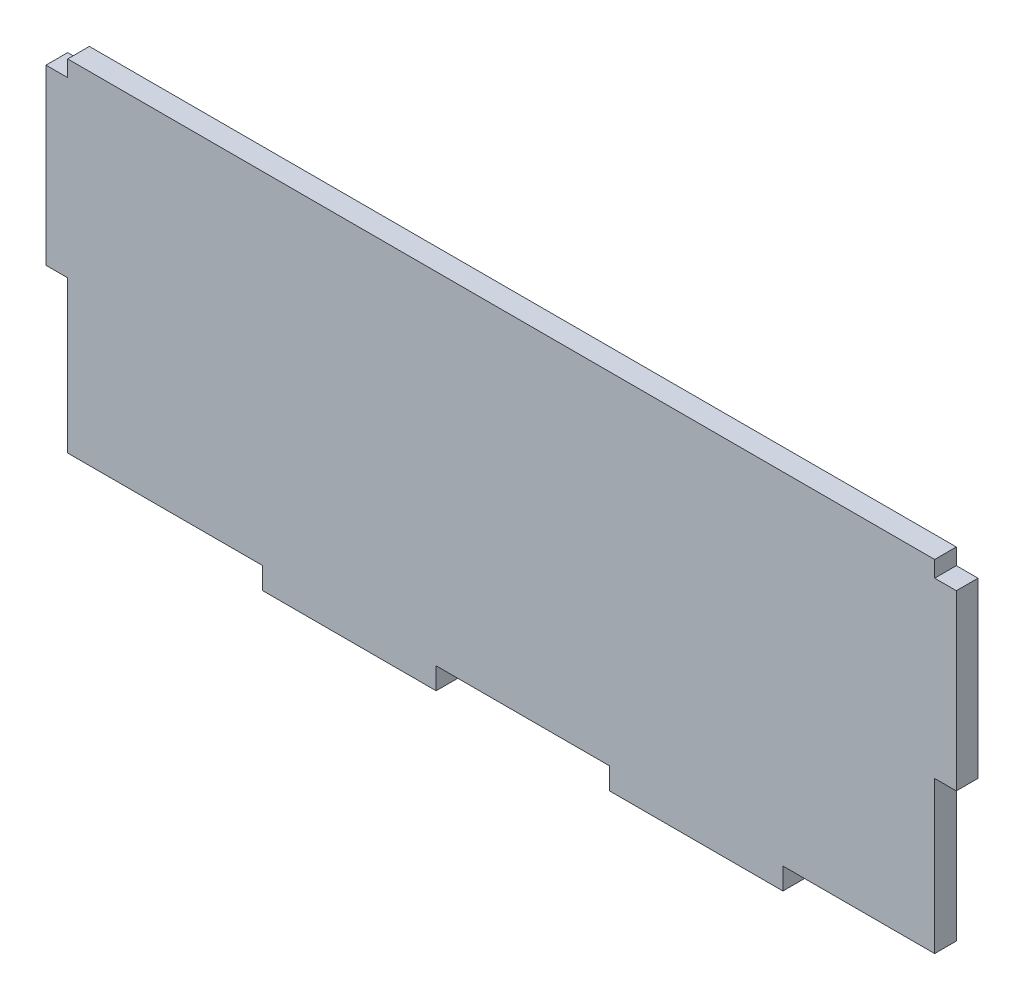
SolidWorks part; units mm, degrees
ref_plane "Front Plane" through (0, 0, 0) normal (0, 0, 1) x (1, 0, 0)
ref_plane "Top Plane" through (0, 0, 0) normal (0, 1, 0) x (1, 0, 0)
ref_plane "Right Plane" through (0, 0, 0) normal (1, 0, 0) x (0, 0, -1)
sketch "Sketch1" plane through (0, 0, 0) normal (0, 0, 1) x (1, 0, 0)
  line L0 (0, 0) -> (0, 44.45)
  line L1 (0, 0) -> (254, 0) construction
  line L2 (0, 0) -> (0, 100) construction
  line L3 (0, 100) -> (254, 100)
  line L4 (254, 0) -> (254, 100) construction
  line L5 (0, 0) -> (254, 100) construction
  line L6 (0, 100) -> (254, 0) construction
  line L7 (0, 44.45) -> (-6.35, 44.45)
  line L8 (-6.35, 44.45) -> (-6.35, 95.25)
  line L9 (-6.35, 95.25) -> (0, 95.25)
  line L10 (0, 95.25) -> (0, 100)
  line L11 (127, 0) -> (127, 100) construction
  line L12 (254, 0) -> (254, 44.45)
  line L13 (254, 44.45) -> (260.35, 44.45)
  line L14 (260.35, 44.45) -> (260.35, 95.25)
  line L15 (254, 95.25) -> (254, 100)
  line L16 (260.35, 95.25) -> (254, 95.25)
  line L17 (254, 0) -> (209.55, 0)
  line L18 (209.55, 0) -> (209.55, -6.35)
  line L19 (209.55, -6.35) -> (158.75, -6.35)
  line L20 (158.75, -6.35) -> (158.75, 0)
  line L21 (158.75, 0) -> (107.95, 0)
  line L22 (107.95, 0) -> (107.95, -6.35)
  line L23 (107.95, -6.35) -> (57.15, -6.35)
  line L24 (57.15, -6.35) -> (57.15, 0)
  line L25 (57.15, 0) -> (0, 0)
  point P4 (127, 50)
  dimension "D1" = 254
  dimension "D2" = 100
  dimension "D3" = 44.45
  dimension "D4" = 6.35
  dimension "D5" = 50.8
  dimension "D6" = 44.45
  dimension "D7" = 6.35
  dimension "D8" = 50.8
extrude "Boss-Extrude1" add sketch "Sketch1" along normal blind 6.35
